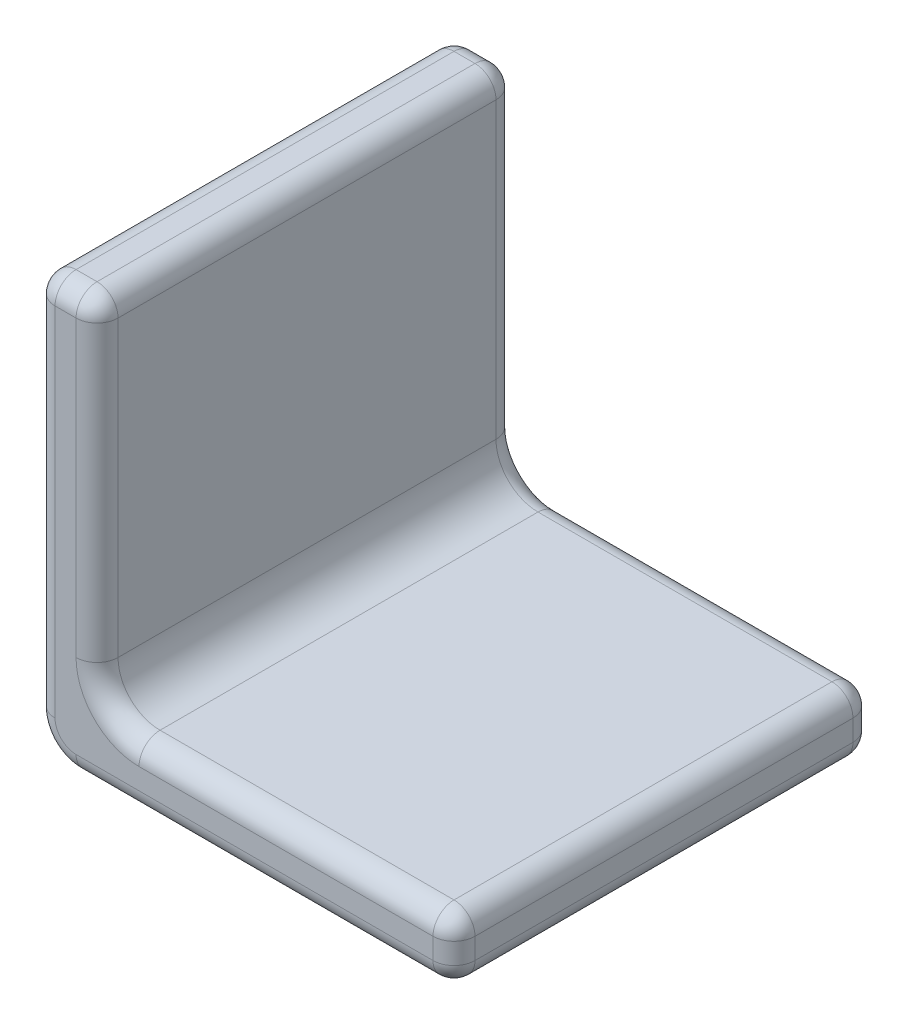
SolidWorks part; units mm, degrees
ref_plane "Front Plane" through (0, 0, 0) normal (0, 0, 1) x (1, 0, 0)
ref_plane "Top Plane" through (0, 0, 0) normal (0, 1, 0) x (1, 0, 0)
ref_plane "Right Plane" through (0, 0, 0) normal (1, 0, 0) x (0, 0, -1)
sketch "Sketch1" plane through (0, 0, 0) normal (0, 0, 1) x (1, 0, 0)
  line L1 (5.6792, 0) -> (19, 0)
  line L3 (5, 3) -> (19, 3)
  line L4 (20, 1) -> (20, 2)
  line L5 (2, 0) -> (5.6792, 0)
  line L6 (0, 2) -> (0, 19)
  line L7 (1, 20) -> (2, 20)
  line L8 (3, 5) -> (3, 19)
  arc A0 (3, 5) -> (5, 3) centre (5, 5) ccw
  arc A1 (0, 2) -> (2, 0) centre (2, 2) ccw
  arc A2 (19, 0) -> (20, 1) centre (19, 1) ccw
  arc A3 (19, 3) -> (20, 2) centre (19, 2) cw
  arc A4 (2, 20) -> (3, 19) centre (2, 19) cw
  arc A5 (0, 19) -> (1, 20) centre (1, 19) cw
  point P12 (0, 0)
  point P15 (20, 0)
  point P18 (20, 3)
  point P21 (3, 20)
  point P24 (0, 20)
  dimension "D5" = 2
  dimension "D6" = 1
  dimension "D1" = 20
  dimension "D2" = 20
  dimension "D3" = 3
  dimension "D4" = 3
extrude "Boss-Extrude1" add sketch "Sketch1" along normal blind 20
fillet "Fillet1" radius 1 24 edges at (3, 12, 0) (2.7071, 19.7071, 0) (1.5, 20, 0) (0.2929, 19.7071, 0) (0, 10.5, 0) (0.5858, 0.5858, 0) (10.5, 0, 0) (19.7071, 0.2929, 0) (20, 1.5, 0) (19.7071, 2.7071, 0) (12, 3, 0) (3.5858, 3.5858, 0) (12, 3, 20) (19.7071, 2.7071, 20) (20, 1.5, 20) (19.7071, 0.2929, 20) (10.5, 0, 20) (0.5858, 0.5858, 20) (0, 10.5, 20) (0.2929, 19.7071, 20) (1.5, 20, 20) (2.7071, 19.7071, 20) (3, 12, 20) (3.5858, 3.5858, 20)
equation "\"D4@Sketch1\"=\"D3@Sketch1\""
